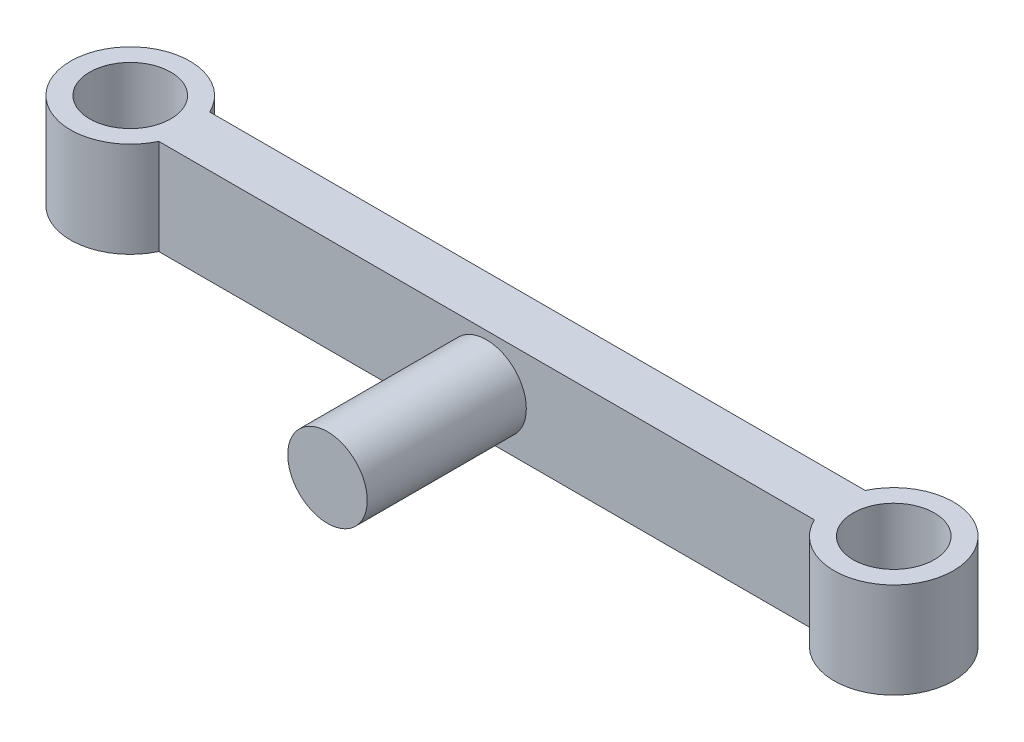
SolidWorks part; units mm, degrees
ref_plane "Front Plane" through (0, 0, 0) normal (0, 0, 1) x (1, 0, 0)
ref_plane "Top Plane" through (0, 0, 0) normal (0, 1, 0) x (1, 0, 0)
ref_plane "Right Plane" through (0, 0, 0) normal (1, 0, 0) x (0, 0, -1)
sketch "Sketch1" plane through (0, 0, 0) normal (0, 1, 0) x (1, 0, 0)
  line L0 (0, 0) -> (0, 38.7787) construction
  circle A0 centre (60, 0) radius 6.375
  circle A1 centre (-60, 0) radius 9.375
  circle A2 centre (60, 0) radius 9.375
  circle A3 centre (-60, 0) radius 6.375
  point P9 (0, 0)
  dimension "D1" = 12.75
  dimension "D2" = 60
  dimension "D3" = 3
extrude "Boss-Extrude1" add sketch "Sketch1" along normal mid plane 15
sketch "Sketch2" plane through (0, 0, 0) normal (1, 0, 0) x (0, 0, -1)
  line L0 (-6.375, -7.5) -> (6.375, -7.5) construction
  line L1 (-4, 7.5) -> (4, 7.5)
  line L2 (-4, 7.5) -> (-4, -7.5)
  line L3 (-4, -7.5) -> (4, -7.5)
  line L4 (4, 7.5) -> (4, -7.5)
  line L5 (6.375, 7.5) -> (-6.375, 7.5) construction
  point P8 (0, 7.5)
  dimension "D1" = 8
extrude "Boss-Extrude2" add sketch "Sketch2" along normal up to next and the other way up to next
sketch "Sketch4" plane through (0, 0, 4) normal (0, 0, 1) x (1, 0, 0)
  circle A0 centre (0, 0) radius 6.25
  dimension "D1" = 12.5
extrude "Boss-Extrude3" add sketch "Sketch4" along normal blind 25
sketch "Sketch5" plane through (0, 0, 0) normal (1, 0, 0) x (0, 0, -1)
  line L0 (-9.375, -7.5) -> (9.375, -7.5) construction
  line L1 (-26, -4.5) -> (-18, -4.5)
  line L2 (-26, -4.5) -> (-26, -7.5)
  line L3 (-26, -7.5) -> (-18, -7.5)
  line L4 (-18, -4.5) -> (-18, -7.5)
  point P6 (-22, -7.5)
  dimension "D1" = 22
  dimension "D2" = 8
  dimension "D3" = 3
extrude "Cut-Extrude1" cut sketch "Sketch5" against normal up to next and the other way up to next
